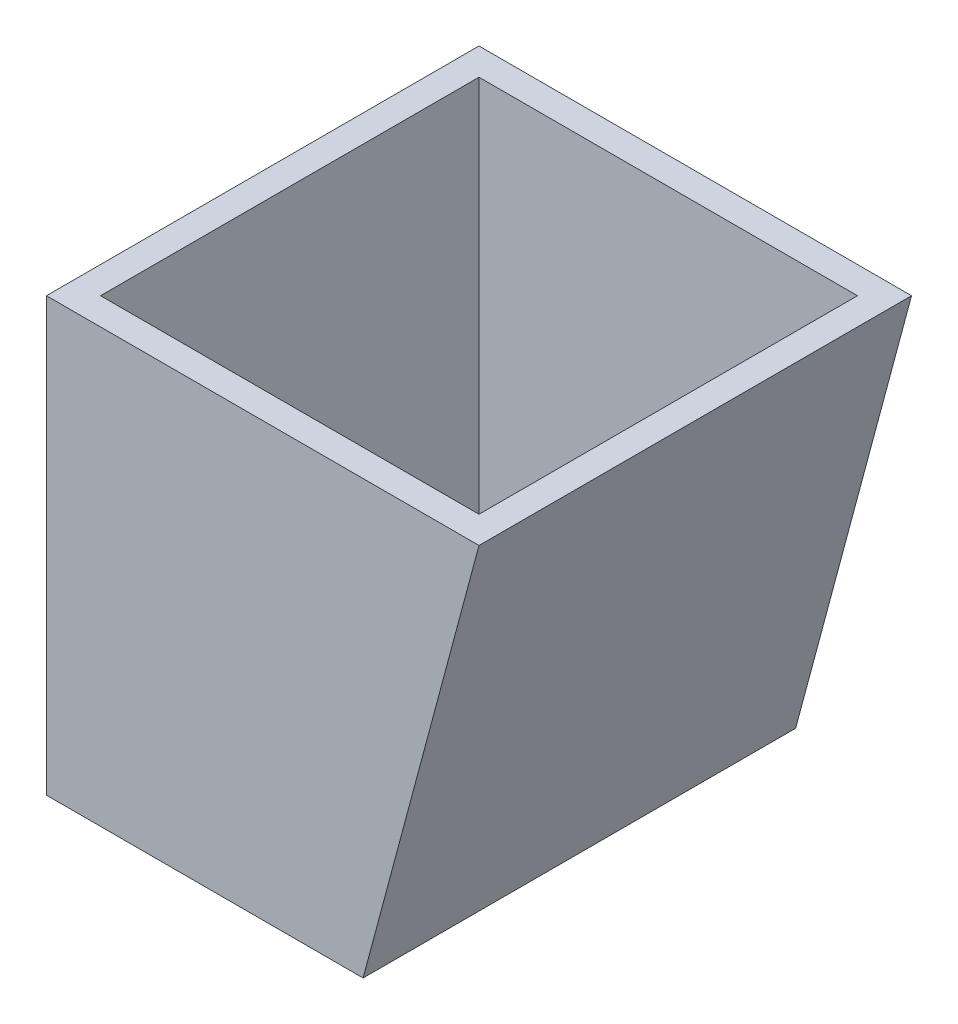
SolidWorks part; units mm, degrees
material "ABS PC"
ref_plane "Front Plane" through (0, 0, 0) normal (0, 0, 1) x (1, 0, 0)
ref_plane "Top Plane" through (0, 0, 0) normal (0, 1, 0) x (1, 0, 0)
ref_plane "Right Plane" through (0, 0, 0) normal (1, 0, 0) x (0, 0, -1)
sketch "Sketch10" plane through (0, 0, 0) normal (0, 1, 0) x (1, 0, 0)
  line L1 (-25.4, 25.4) -> (25.4, 25.4)
  line L2 (-25.4, 25.4) -> (-25.4, -25.4)
  line L3 (-25.4, -25.4) -> (25.4, -25.4)
  line L4 (25.4, 25.4) -> (25.4, -25.4)
  line L5 (-25.4, 25.4) -> (25.4, -25.4) construction
  line L6 (-25.4, -25.4) -> (25.4, 25.4) construction
  point P0 (0, 0)
  point P6 (0, 0)
  dimension "D1" = 50.8
  dimension "D2" = 50.8
extrude "Boss-Extrude4" add sketch "Sketch10" along normal blind 50.8
sketch "Sketch12" plane through (0, 0, 0) normal (0, -1, 0) x (1, 0, 0)
  line L0 (-25.4, 25.4) -> (25.4, 25.4) construction
  line L1 (-22.225, 22.225) -> (22.225, 22.225)
  line L2 (-22.225, 22.225) -> (-22.225, -22.225)
  line L3 (-22.225, -22.225) -> (22.225, -22.225)
  line L4 (22.225, 22.225) -> (22.225, -22.225)
  line L5 (-22.225, 22.225) -> (22.225, -22.225) construction
  line L6 (-22.225, -22.225) -> (22.225, 22.225) construction
  line L7 (25.4, 25.4) -> (25.4, -25.4) construction
  point P0 (0, 0)
  dimension "D1" = 3.175
  dimension "D2" = 3.175
sketch "Sketch16" plane through (0, 0, 25.4) normal (0, 0, 1) x (1, 0, 0)
  line L1 (8.6132, 0) -> (22.225, 50.8)
  line L2 (-25.4, 50.8) -> (25.4, 50.8) construction
  line L5 (22.225, 50.8) -> (25.4, 50.8)
  line L8 (-25.4, 0) -> (25.4, 0) construction
  line L9 (11.7882, 0) -> (8.6132, 0)
  line L10 (25.4, 50.8) -> (11.7882, 0)
  line L11 (25.4, 50.8) -> (25.4, 0) construction
  dimension "D1" = 15
  dimension "D2" = 3.175
sketch "Sketch17" plane through (0, 0, 25.4) normal (0, 0, 1) x (1, 0, 0)
  line L0 (25.4, 50.8) -> (11.7882, 0) construction
  line L1 (25.4, 0) -> (25.4, 50.8)
  line L2 (11.7882, 0) -> (25.4, 0)
  line L4 (22.225, 50.8) -> (8.6132, 0)
  line L5 (25.4, 50.8) -> (22.225, 50.8)
  line L6 (11.7882, 0) -> (25.4, 50.8)
  line L7 (8.6132, 0) -> (11.7882, 0)
  line L10 (11.7882, 0) -> (25.4, 50.8)
  dimension "D1" = 0
extrude "Cut-Extrude6" cut sketch "Sketch17" against normal through all
sketch "Sketch19" plane through (0, 50.8, 0) normal (0, 1, 0) x (1, 0, 0)
  line L0 (25.4, 25.4) -> (-25.4, 25.4) construction
  line L1 (-22.225, 22.225) -> (22.225, 22.225)
  line L2 (-22.225, 22.225) -> (-22.225, -22.225)
  line L3 (-22.225, -22.225) -> (22.225, -22.225)
  line L4 (22.225, 22.225) -> (22.225, -22.225)
  line L5 (-22.225, 22.225) -> (22.225, -22.225) construction
  line L6 (-22.225, -22.225) -> (22.225, 22.225) construction
  line L7 (25.4, -25.4) -> (25.4, 25.4) construction
  point P0 (0, 0)
  dimension "D1" = 3.175
  dimension "D2" = 3.175
extrude "Cut-Extrude8" cut sketch "Sketch19" against normal blind 47.625
sketch "Sketch20" plane through (0, 0, 25.4) normal (0, 0, 1) x (1, 0, 0)
  line L4 (22.225, 50.8) -> (8.6132, 0)
  line L5 (25.4, 50.8) -> (22.225, 50.8)
  line L6 (11.7882, 0) -> (25.4, 50.8)
  line L7 (8.6132, 0) -> (11.7882, 0)
  line L8 (22.225, 50.8) -> (8.6132, 0)
  line L9 (25.4, 50.8) -> (22.225, 50.8)
  line L10 (11.7882, 0) -> (25.4, 50.8)
  line L11 (8.6132, 0) -> (11.7882, 0)
  dimension "D1" = 0
extrude "Boss-Extrude6" add sketch "Sketch20" against normal blind 47.625
